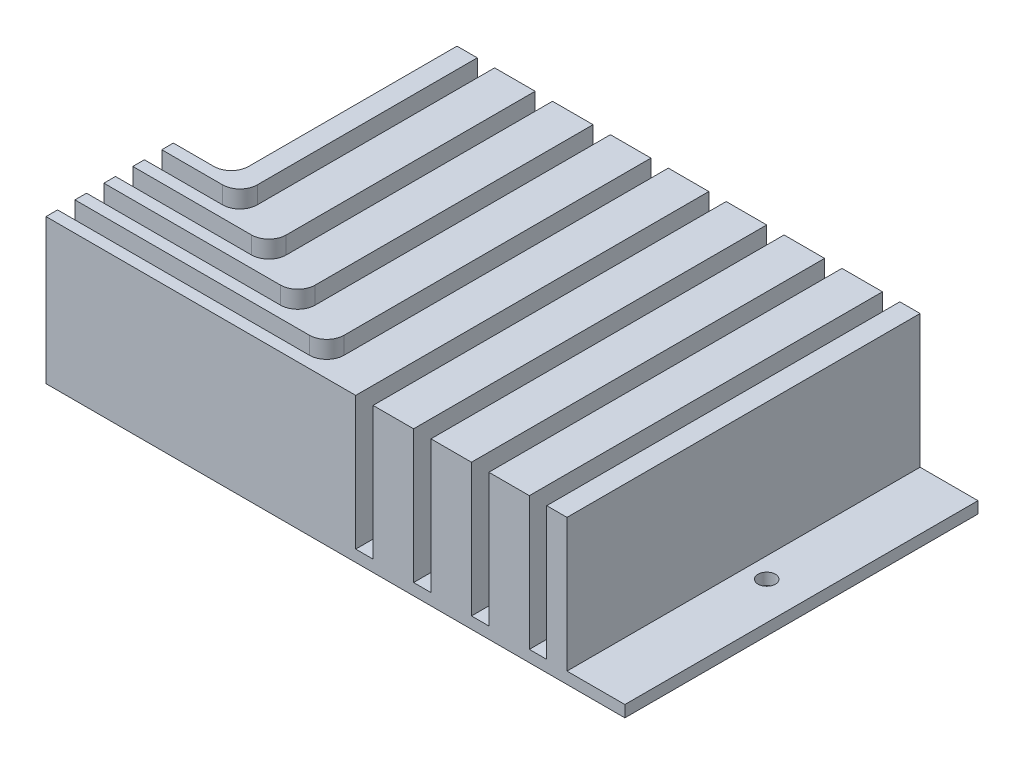
SolidWorks part; units mm, degrees
ref_plane "Front Plane" through (0, 0, 0) normal (0, 0, 1) x (1, 0, 0)
ref_plane "Top Plane" through (0, 0, 0) normal (0, 1, 0) x (1, 0, 0)
ref_plane "Right Plane" through (0, 0, 0) normal (1, 0, 0) x (0, 0, -1)
sketch "ProfileSketch1" plane through (0, 0, 0) normal (0, 1, 0) x (1, 0, 0)
  line L1 (0, 0) -> (100, 0)
  line L6 (0, 61) -> (100, 61)
  line L7 (100, 61) -> (100, 0)
  line L8 (0, 61) -> (0, 0)
  dimension "D2" = 61
  dimension "D1" = 100
extrude "ProfileBoss-Extrude1" add sketch "ProfileSketch1" along normal blind 25
sketch "Cable GuidesSketch2" plane through (0, 25, 0) normal (0, 1, 0) x (1, 0, 0)
  line L0 (100, 61) -> (0, 61) construction
  line L1 (43.5, 61) -> (46.5, 61)
  line L2 (43.5, 61) -> (43.5, 5)
  line L4 (46.5, 61) -> (46.5, 2)
  line L6 (46.5, 2) -> (0, 2)
  line L8 (0, 20) -> (0, 17)
  line L11 (0, 5) -> (43.5, 5)
  line L12 (0, 0) -> (100, 0) construction
  line L13 (0, 5) -> (0, 2)
  line L15 (0, 7) -> (36.5, 7)
  line L16 (36.5, 7) -> (36.5, 61)
  line L17 (36.5, 61) -> (33.5, 61)
  line L18 (33.5, 61) -> (33.5, 10)
  line L19 (33.5, 10) -> (0, 10)
  line L23 (0, 12) -> (26.5, 12)
  line L24 (26.5, 12) -> (26.5, 61)
  line L25 (26.5, 61) -> (23.5, 61)
  line L26 (23.5, 61) -> (23.5, 15)
  line L27 (23.5, 15) -> (0, 15)
  line L31 (0, 17) -> (16.5, 17)
  line L35 (16.5, 17) -> (16.5, 61)
  line L36 (16.5, 61) -> (13.5, 61)
  line L37 (13.5, 61) -> (13.5, 20)
  line L38 (13.5, 20) -> (0, 20)
  line L39 (0, 15) -> (0, 12)
  line L40 (0, 10) -> (0, 7)
  line L41 (0, 61) -> (0, 0) construction
  line L42 (100, 61) -> (0, 61) construction
  line L43 (53.5, 61) -> (56.5, 61)
  line L44 (53.5, 61) -> (53.5, 0)
  line L45 (53.5, 0) -> (56.5, 0)
  line L46 (56.5, 61) -> (56.5, 0)
  line L47 (0, 0) -> (100, 0) construction
  line L48 (100, 0) -> (100, 61) construction
  line L49 (63.5, 61) -> (66.5, 61)
  line L50 (63.5, 61) -> (63.5, 0)
  line L51 (63.5, 0) -> (66.5, 0)
  line L52 (66.5, 61) -> (66.5, 0)
  line L53 (73.5, 61) -> (76.5, 61)
  line L54 (73.5, 61) -> (73.5, 0)
  line L55 (73.5, 0) -> (76.5, 0)
  line L56 (76.5, 61) -> (76.5, 0)
  line L57 (83.5, 61) -> (86.5, 61)
  line L58 (83.5, 61) -> (83.5, 0)
  line L59 (83.5, 0) -> (86.5, 0)
  line L60 (86.5, 61) -> (86.5, 0)
  point P26 (43.5, 33)
  dimension "D1" = 3
  dimension "D4" = 2
  dimension "D6" = 2
  dimension "D7" = 7
  dimension "D11" = 7
  dimension "D12" = 2
  dimension "D14" = 7
  dimension "D15" = 2
  dimension "D2" = 13.5
  dimension "D3" = 7
  dimension "D5" = 7
  dimension "D8" = 7
  dimension "D9" = 7
  dimension "D10" = 13.5
extrude "CableGuidesCut-Extrude1" cut sketch "Cable GuidesSketch2" against normal blind 23
sketch "FastenerTabSketch1" plane through (0, 25, 0) normal (0, 1, 0) x (1, 0, 0)
  line L0 (13.5, 20) -> (0, 20) construction
  line L1 (0, 61) -> (10, 61)
  line L2 (0, 61) -> (0, 22)
  line L3 (0, 22) -> (10, 22)
  line L4 (10, 61) -> (10, 22)
  line L5 (13.5, 61) -> (13.5, 20) construction
  line L7 (90, 61) -> (100, 61)
  line L8 (90, 61) -> (90, 0)
  line L9 (90, 0) -> (100, 0)
  line L10 (100, 61) -> (100, 0)
  line L15 (100, 0) -> (100, 61) construction
  point P5 (5, 22)
  dimension "D1" = 2
  dimension "D2" = 3.5
sketch "FasteningHoleSketch2" plane through (0, 25, 0) normal (0, 1, 0) x (1, 0, 0)
  line L0 (100, 0) -> (100, 61) construction
  line L2 (0, 61) -> (0, 20) construction
  line L3 (13.5, 61) -> (0, 61) construction
  circle A0 centre (6.5, 31) radius 1.5
  circle A1 centre (93.5, 31) radius 1.5
  dimension "D1" = 3
  dimension "D2" = 6.5
  dimension "D3" = 6.5
  dimension "D4" = 30
extrude "FastenerTabCut-Extrude1" cut sketch "FastenerTabSketch1" against normal blind 23
extrude "FasteningHoleCut-Extrude2" cut sketch "FasteningHoleSketch2" against normal through all
fillet "Fillet1" radius 3 4 edges at (43.5, 13.5, -5) (33.5, 13.5, -10) (23.5, 13.5, -15) (13.5, 13.5, -20)
fillet "Fillet2" radius 3 5 edges at (46.5, 13.5, -2) (36.5, 13.5, -7) (26.5, 13.5, -12) (16.5, 13.5, -17) (10, 13.5, -22)
equation "\"PowerCableGuideOctopusWidth\"= \"DistanceBetweenPowerSupplyLeads\" * \"NumberOfOctopusLeads\" + \"MountingHoleTabWidth\" * 2"
equation "\"CableGuideOffset\"= 60mm"
equation "\"CableDiameter\"= 3mm"
equation "\"D1@Cable GuidesSketch2\" = \"CableDiameter\""
equation "\"D4@Cable GuidesSketch2\"=2mm"
equation "\"D6@Cable GuidesSketch2\" = 2mm"
equation "\"D12@Cable GuidesSketch2\"=2mm"
equation "\"ExtraShortHeight\"= 10mm"
equation "\"D2@ProfileSketch1\"= ( \"NumberOfOctopusLeads\" * \"CableDiameter\" ) * 2 + \"CableDiameter\" + \"ExtraShortHeight\""
equation "\"D1@CableGuidesCut-Extrude1\"=\"OctopusCableGuideDepth\"- 2mm"
equation "\"M3HoleDiameter\"=3"
equation "\"DistanceBetweenPowerSupplyLeads\"= 10mm'Spec"
equation "\"D14@Cable GuidesSketch2\"=\"DistanceBetweenPowerSupplyLeads\"-\"CableDiameter\""
equation "\"D11@Cable GuidesSketch2\"=\"DistanceBetweenPowerSupplyLeads\"-\"CableDiameter\""
equation "\"D7@Cable GuidesSketch2\"=\"DistanceBetweenPowerSupplyLeads\"-\"CableDiameter\""
equation "\"CableGuideCableOffset\"=3.5"
equation "\"OctopusCableGuideDepth\" = 25mm"
equation "\"D1@ProfileBoss-Extrude1\"=\"OctopusCableGuideDepth\""
equation "\"NumberOfOctopusLeads\" = 8"
equation "\"D1@ProfileSketch1\"=\"PowerCableGuideOctopusWidth\""
equation "\"MountingHoleTabWidth\"= 10mm"
equation "\"D2@FastenerTabSketch1\" =  ( \"DistanceBetweenPowerSupplyLeads\" - \"CableDiameter\" )  / 2"
equation "\"D1@FasteningHoleSketch2\" = \"M3HoleDiameter\""
equation "\"D1@FastenerTabCut-Extrude1\" = \"OctopusCableGuideDepth\" - 2mm"
equation "\"D3@Cable GuidesSketch2\"=\"DistanceBetweenPowerSupplyLeads\"-\"CableDiameter\""
equation "\"D5@Cable GuidesSketch2\"=\"DistanceBetweenPowerSupplyLeads\"-\"CableDiameter\""
equation "\"D8@Cable GuidesSketch2\"=\"DistanceBetweenPowerSupplyLeads\"-\"CableDiameter\""
equation "\"D9@Cable GuidesSketch2\"=\"DistanceBetweenPowerSupplyLeads\"-\"CableDiameter\""
equation "\"D2@Cable GuidesSketch2\"=(\"DistanceBetweenPowerSupplyLeads\"-\"M3HoleDiameter\")/2 + \"MountingHoleTabWidth\""
equation "\"D2@FasteningHoleSketch2\"=(\"MountingHoleTabWidth\" + \"M3HoleDiameter\") /2"
equation "\"D3@FasteningHoleSketch2\"=(\"MountingHoleTabWidth\" + \"M3HoleDiameter\")/2"
equation "\"D4@FasteningHoleSketch2\"=\"CableGuideOffset\"/2"
